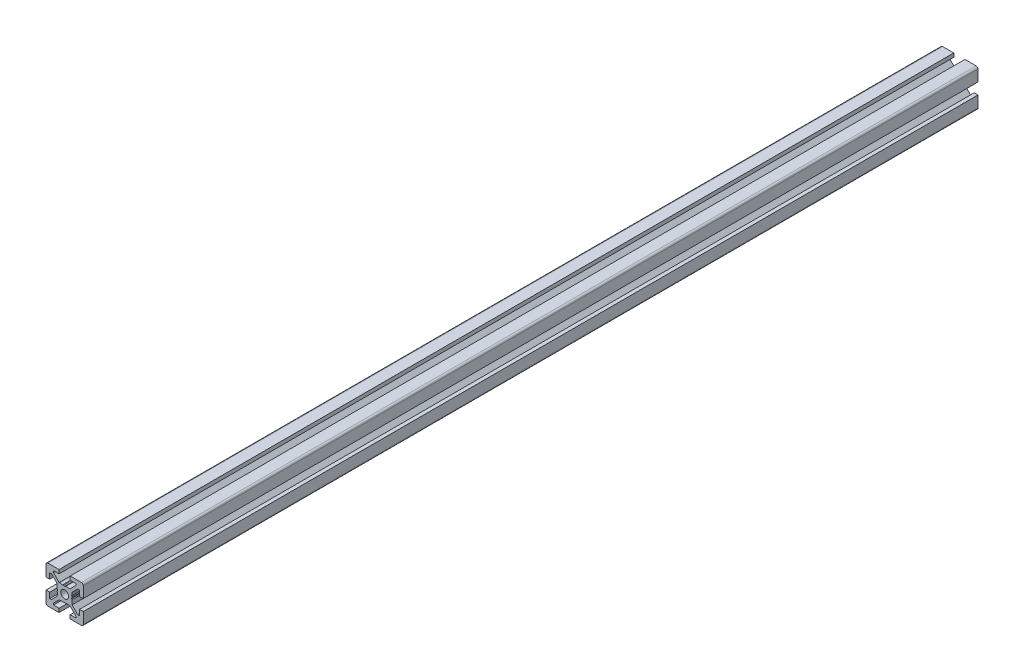
SolidWorks part; units mm, degrees
ref_plane "Front Plane" through (0, 0, 0) normal (0, 0, 1) x (1, 0, 0)
ref_plane "Top Plane" through (0, 0, 0) normal (0, 1, 0) x (1, 0, 0)
ref_plane "Right Plane" through (0, 0, 0) normal (1, 0, 0) x (0, 0, -1)
ref_plane "Plane1" through (0, 0, -2000) normal (0, 0, -1) x (-1, 0, 0)
sketch "Sketch1" plane through (0, 0, -2000) normal (0, 0, -1) x (-1, 0, 0)
  line L0 (10, -3) -> (8, -3)
  line L1 (8, -3) -> (8, -6)
  line L2 (8, -6) -> (7.0607, -6)
  line L3 (7.0607, -6) -> (4, -2.9393)
  line L4 (4, -2.9393) -> (4, -2.5)
  line L5 (4, -2.5) -> (3.751, -1.2189)
  line L6 (3.751, -1.2189) -> (3.933, -0.9036)
  line L7 (3.933, -0.4036) -> (3.7, 0)
  line L8 (3.7, 0) -> (3.933, 0.4036)
  line L9 (4, 0.6536) -> (4, 2.9393)
  line L10 (4, 2.9393) -> (7.0607, 6)
  line L11 (7.0607, 6) -> (8, 6)
  line L12 (8, 6) -> (8, 3)
  line L13 (8, 3) -> (10, 3)
  line L14 (10, 3) -> (10, 9)
  line L15 (9, 10) -> (3, 10)
  line L16 (3, 10) -> (3, 8)
  line L17 (3, 8) -> (6, 8)
  line L18 (6, 8) -> (6, 7.0607)
  line L19 (6, 7.0607) -> (2.9393, 4)
  line L20 (2.9393, 4) -> (2.5, 4)
  line L21 (2.5, 4) -> (1.2189, 3.751)
  line L22 (1.2189, 3.751) -> (0.9036, 3.933)
  line L23 (0.4036, 3.933) -> (0, 3.7)
  line L24 (0, 3.7) -> (-0.4036, 3.933)
  line L25 (-0.6536, 4) -> (-2.9393, 4)
  line L26 (-2.9393, 4) -> (-6, 7.0607)
  line L27 (-6, 7.0607) -> (-6, 8)
  line L28 (-6, 8) -> (-3, 8)
  line L29 (-3, 8) -> (-3, 10)
  line L30 (-3, 10) -> (-9, 10)
  line L31 (-10, 9) -> (-10, 3)
  line L32 (-10, 3) -> (-8, 3)
  line L33 (-8, 3) -> (-8, 6)
  line L34 (-8, 6) -> (-7.0607, 6)
  line L35 (-7.0607, 6) -> (-4, 2.9393)
  line L36 (-4, 2.9393) -> (-4, 2.5)
  line L37 (-4, 2.5) -> (-3.751, 1.2189)
  line L38 (-3.751, 1.2189) -> (-3.933, 0.9036)
  line L39 (-3.933, 0.4036) -> (-3.7, 0)
  line L40 (-3.7, 0) -> (-3.933, -0.4036)
  line L41 (-4, -0.6536) -> (-4, -2.9393)
  line L42 (-4, -2.9393) -> (-7.0607, -6)
  line L43 (-7.0607, -6) -> (-8, -6)
  line L44 (-8, -6) -> (-8, -3)
  line L45 (-8, -3) -> (-10, -3)
  line L46 (-10, -3) -> (-10, -9)
  line L47 (-9, -10) -> (-3, -10)
  line L48 (-3, -10) -> (-3, -8)
  line L49 (-3, -8) -> (-6, -8)
  line L50 (-6, -8) -> (-6, -7.0607)
  line L51 (-6, -7.0607) -> (-2.9393, -4)
  line L52 (-2.9393, -4) -> (-2.5, -4)
  line L53 (-2.5, -4) -> (-1.2189, -3.751)
  line L54 (-1.2189, -3.751) -> (-0.9036, -3.933)
  line L55 (-0.4036, -3.933) -> (0, -3.7)
  line L56 (0, -3.7) -> (0.4036, -3.933)
  line L57 (0.6536, -4) -> (2.9393, -4)
  line L58 (2.9393, -4) -> (6, -7.0607)
  line L59 (6, -7.0607) -> (6, -8)
  line L60 (6, -8) -> (3, -8)
  line L61 (3, -8) -> (3, -10)
  line L62 (3, -10) -> (9, -10)
  line L63 (10, -9) -> (10, -3)
  circle A0 centre (0, 0) radius 2.1
  arc A1 (3.933, -0.9036) -> (3.933, -0.4036) centre (3.5, -0.6536) ccw
  arc A2 (3.933, 0.4036) -> (4, 0.6536) centre (3.5, 0.6536) ccw
  arc A3 (10, 9) -> (9, 10) centre (9, 9) ccw
  arc A4 (0.9036, 3.933) -> (0.4036, 3.933) centre (0.6536, 3.5) ccw
  arc A5 (-0.4036, 3.933) -> (-0.6536, 4) centre (-0.6536, 3.5) ccw
  arc A6 (-9, 10) -> (-10, 9) centre (-9, 9) ccw
  arc A7 (-3.933, 0.9036) -> (-3.933, 0.4036) centre (-3.5, 0.6536) ccw
  arc A8 (-3.933, -0.4036) -> (-4, -0.6536) centre (-3.5, -0.6536) ccw
  arc A9 (-10, -9) -> (-9, -10) centre (-9, -9) ccw
  arc A10 (-0.9036, -3.933) -> (-0.4036, -3.933) centre (-0.6536, -3.5) ccw
  arc A11 (0.4036, -3.933) -> (0.6536, -4) centre (0.6536, -3.5) ccw
  arc A12 (9, -10) -> (10, -9) centre (9, -9) ccw
extrude "Boss-Extrude1" add sketch "Sketch1" against normal blind 480
